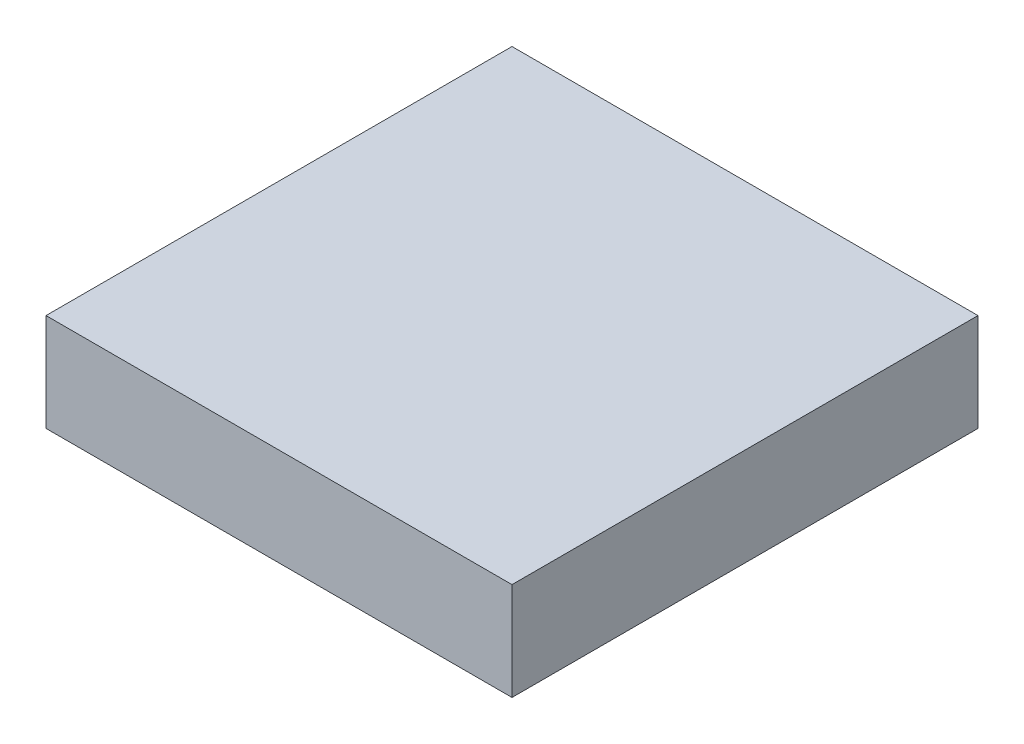
SolidWorks part; units mm, degrees
ref_plane "Front Plane" through (0, 0, 0) normal (0, 0, 1) x (1, 0, 0)
ref_plane "Top Plane" through (0, 0, 0) normal (0, 1, 0) x (1, 0, 0)
ref_plane "Right Plane" through (0, 0, 0) normal (1, 0, 0) x (0, 0, -1)
sketch "Sketch1" plane through (0, 0, 0) normal (0, 1, 0) x (1, 0, 0)
  line L0 (0, 0) -> (2.436, 0)
  line L1 (2.436, 0) -> (2.436, 2.436)
  line L2 (2.436, 2.436) -> (0, 2.436)
  line L3 (0, 2.436) -> (0, 0)
  dimension "D1" = 2.436
  dimension "D2" = 2.436
extrude "Boss-Extrude1" add sketch "Sketch1" along normal blind 0.511
